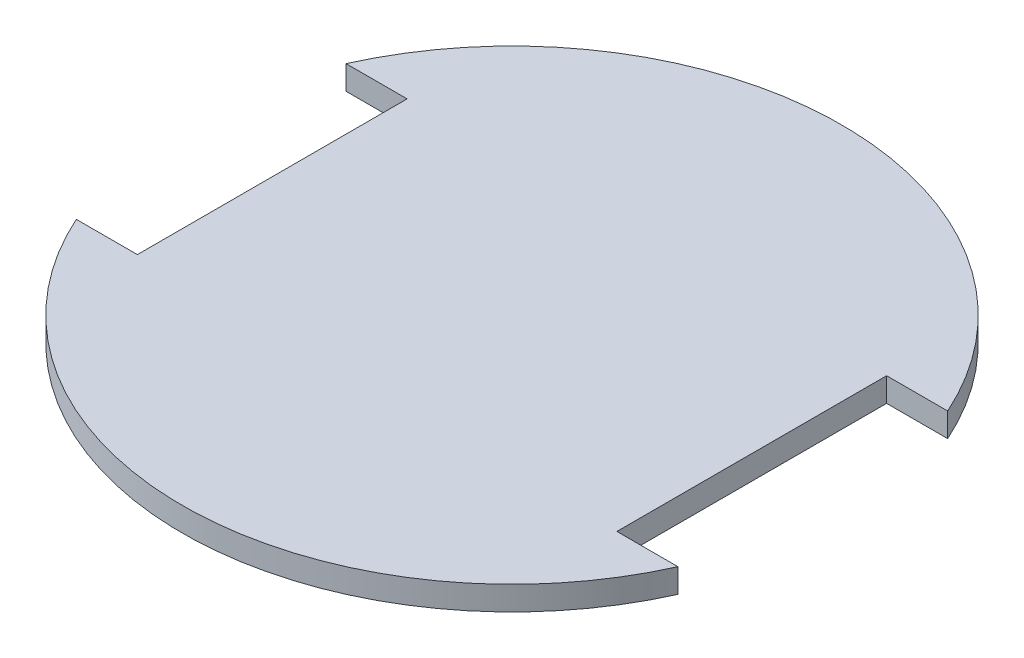
SolidWorks part; units mm, degrees
ref_plane "Plan de face" through (0, 0, 0) normal (0, 0, 1) x (1, 0, 0)
ref_plane "Plan de dessus" through (0, 0, 0) normal (0, 1, 0) x (1, 0, 0)
ref_plane "Plan de droite" through (0, 0, 0) normal (1, 0, 0) x (0, 0, -1)
sketch "Esquisse1" plane through (0, 0, 0) normal (0, 1, 0) x (1, 0, 0)
  line L0 (-80, -75.4983) -> (-80, 75.4983) construction
  line L1 (-80, 45) -> (-80, -45)
  line L2 (-110, 0) -> (110, 0) construction
  line L3 (-80, 45) -> (-100.3743, 45)
  line L4 (-80, -45) -> (-100.3743, -45)
  line L5 (0, 110) -> (0, -110) construction
  line L6 (80, -45) -> (100.3743, -45)
  line L7 (80, 45) -> (80, -45)
  line L8 (80, 45) -> (100.3743, 45)
  circle A0 centre (0, 0) radius 110 construction
  arc A1 (-100.3743, 45) -> (100.3743, 45) centre (0, 0) cw
  arc A2 (100.3743, -45) -> (-100.3743, -45) centre (0, 0) cw
  dimension "D1" = 80
  dimension "D2" = 45
  dimension "D4" = 220
  dimension "D3" = 90
extrude "Boss.-Extru.1" add sketch "Esquisse1" along normal blind 8
